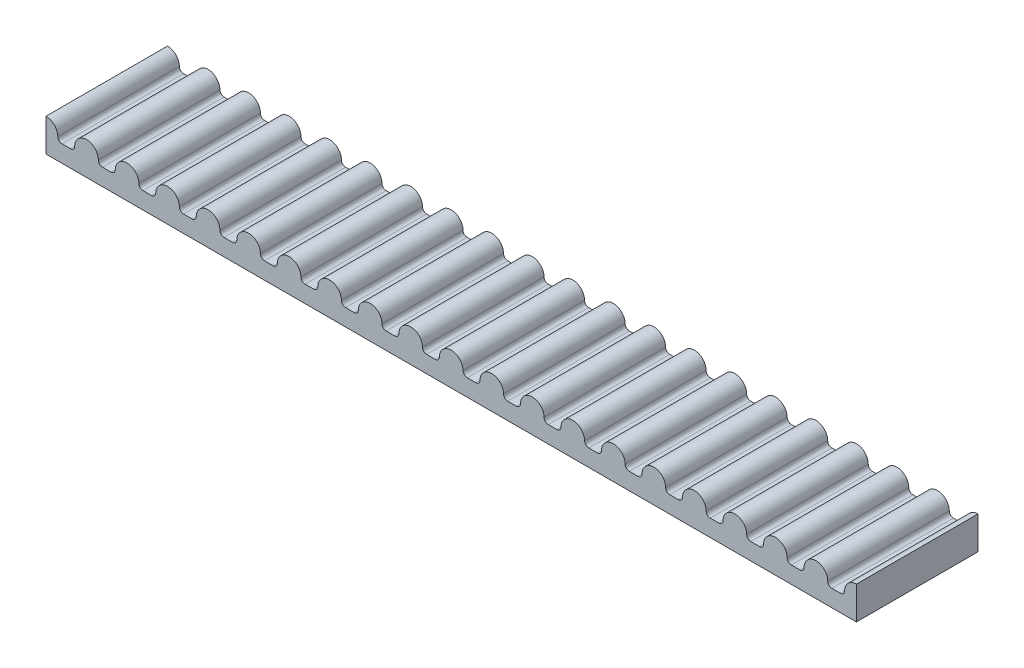
SolidWorks part; units mm, degrees
ref_plane "Front Plane" through (0, 0, 0) normal (0, 0, 1) x (1, 0, 0)
ref_plane "Top Plane" through (0, 0, 0) normal (0, 1, 0) x (1, 0, 0)
ref_plane "Right Plane" through (0, 0, 0) normal (1, 0, 0) x (0, 0, -1)
sketch "Sketch1" plane through (0, 0, 0) normal (0, 0, 1) x (1, 0, 0)
  line L0 (0, 0) -> (3, 0)
  line L2 (3, 1.25) -> (0, 1.25) construction
  line L3 (0, 1.25) -> (0, 0)
  line L4 (0, 2.43) -> (0, 1.25)
  line L5 (3, 2.43) -> (3, 1.25) construction
  line L6 (0.875, 1.555) -> (0.875, 2.43) construction
  line L7 (0.875, 2.43) -> (0, 2.43) construction
  line L8 (2.125, 1.25) -> (2.125, 2.43) construction
  line L9 (2.125, 2.43) -> (3, 2.43) construction
  line L10 (0.875, 2.43) -> (2.125, 2.43) construction
  line L11 (1.5, 2.43) -> (1.5, 1.25) construction
  line L12 (0.875, 2.43) -> (0, 2.43) construction
  line L13 (3, 2.43) -> (3, 0)
  line L14 (1.18, 1.25) -> (1.82, 1.25)
  arc A0 (0.875, 1.555) -> (0, 2.43) centre (0, 1.555) ccw
  arc A1 (0.875, 1.555) -> (1.18, 1.25) centre (1.18, 1.555) ccw
  arc A2 (2.125, 1.555) -> (1.82, 1.25) centre (1.82, 1.555) cw
  arc A3 (2.125, 1.555) -> (3, 2.43) centre (3, 1.555) cw
  dimension "D1" = 1.25
  dimension "D2" = 3
  dimension "D4" = 0.875
  dimension "D5" = 2.43
extrude "Boss-Extrude1" add sketch "Sketch1" along normal blind 9
pattern_linear "LPattern1" count 20 spacing 3 along (-1, 0, 0) of "Boss-Extrude1"
ref_plane "Plane1" through (-27, 0, 0) normal (1, 0, 0) x (0, 0, -1)
ref_plane "Plane2" through (0, 0, 4.5) normal (0, 0, 1) x (1, 0, 0)
